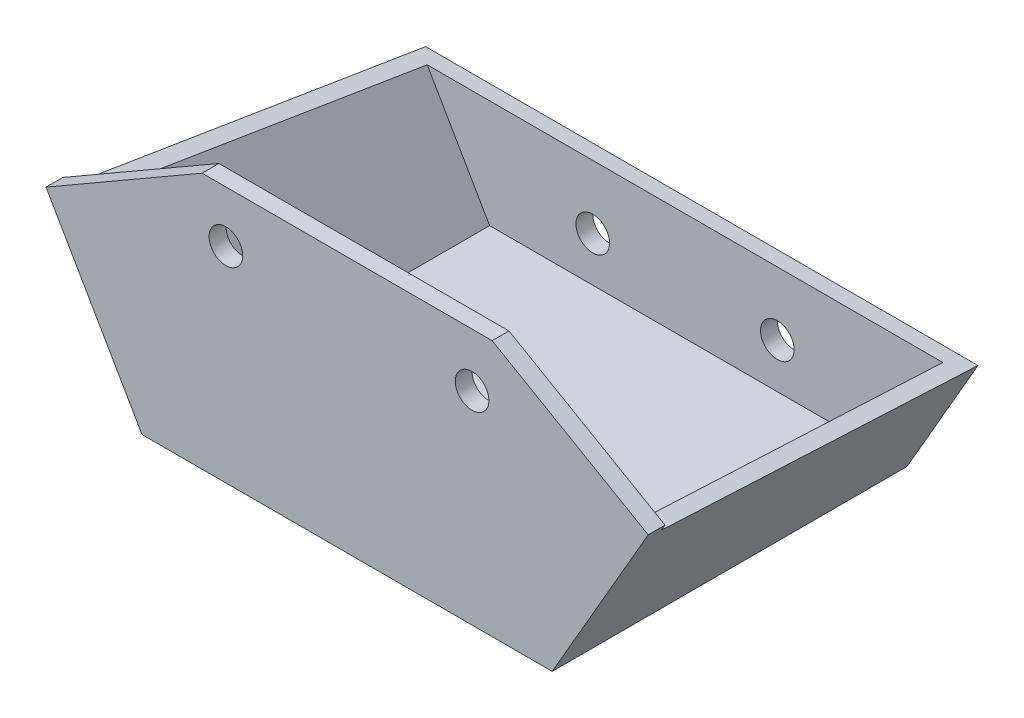
SolidWorks part; units mm, degrees
ref_plane "前视基准面" through (0, 0, 0) normal (0, 0, 1) x (1, 0, 0)
ref_plane "上视基准面" through (0, 0, 0) normal (0, 1, 0) x (1, 0, 0)
ref_plane "右视基准面" through (0, 0, 0) normal (1, 0, 0) x (0, 0, -1)
sketch "草图1" plane through (0, 0, 0) normal (0, 0, 1) x (1, 0, 0)
  line L0 (122, 0) -> (-122, 0)
  line L1 (-122, 0) -> (-179.1007, 98.9013)
  line L2 (-179.1007, 98.9013) -> (-86.265, 152.5)
  line L3 (-86.265, 152.5) -> (86.265, 152.5)
  line L4 (0, 152.5) -> (0, 0) construction
  line L5 (122, 0) -> (179.1007, 98.9013)
  line L6 (179.1007, 98.9013) -> (86.265, 152.5)
  dimension "D1" = 122
  dimension "D2" = 120
  dimension "D3" = 150
  dimension "D4" = 152.5
  dimension "D5" = 86.265
extrude "凸台-拉伸1" add sketch "草图1" along normal blind 211
shell "抽壳1" thickness 10
sketch "草图4" plane through (0, 0, 0) normal (0, 0, -1) x (-1, 0, 0)
  line L0 (0, 0) -> (0, 50.0639) construction
  line L1 (122, 0) -> (-122, 0) construction
  circle A0 centre (-54.9, 36.6) radius 10
  circle A1 centre (54.9, 36.6) radius 10
  dimension "D1" = 20
  dimension "D2" = 109.8
  dimension "D3" = 36.6
extrude "切除-拉伸5" cut sketch "草图4" against normal up to next
sketch "草图5" plane through (0, 0, 211) normal (0, 0, 1) x (1, 0, 0)
  line L0 (0, 0) -> (1.5692, 171.3869) construction
  line L1 (86.265, 152.5) -> (-86.265, 152.5) construction
  circle A0 centre (-72.0891, 122) radius 10
  circle A1 centre (74.3109, 120.6596) radius 10
  dimension "D1" = 20
  dimension "D2" = 30.5
  dimension "D3" = 146.4
extrude "切除-拉伸6" cut sketch "草图5" against normal up to next
sketch "草图7" plane through (0, 0, 0) normal (1, 0, 0) x (0, 0, -1)
  line L0 (0, 73.2) -> (-201, 95.241)
  line L1 (0, 98.9013) -> (0, 0) construction
  line L2 (-201, 95.241) -> (-201, 152.5)
  line L3 (-211, 152.5) -> (0, 152.5) construction
  line L4 (-201, 152.5) -> (0, 152.5)
  line L5 (0, 152.5) -> (0, 73.2)
  dimension "D1" = 73.2
extrude "切除-拉伸9" cut sketch "草图7" against normal through all both and the other way through all
